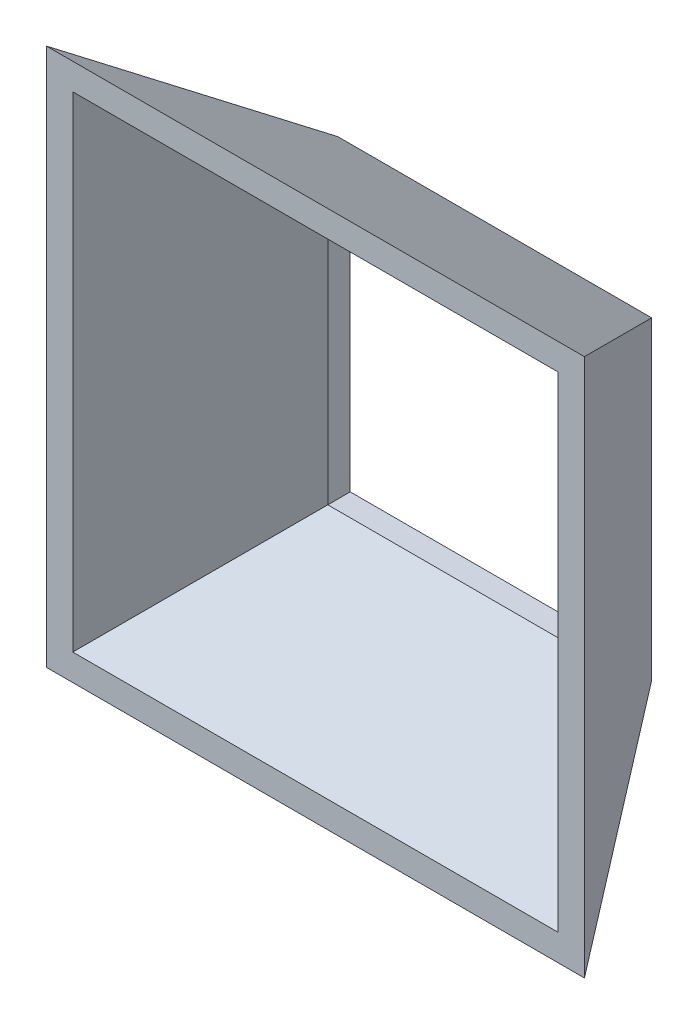
SolidWorks part; units mm, degrees
ref_plane "Front Plane" through (0, 0, 0) normal (0, 0, 1) x (1, 0, 0)
ref_plane "Top Plane" through (0, 0, 0) normal (0, 1, 0) x (1, 0, 0)
ref_plane "Right Plane" through (0, 0, 0) normal (1, 0, 0) x (0, 0, -1)
sketch "Sketch1" plane through (0, 0, 0) normal (0, 0, 1) x (1, 0, 0)
  line L0 (0, 0) -> (0, 0.6682) construction
  line L1 (-44.45, 44.45) -> (44.45, 44.45)
  line L2 (-44.45, 44.45) -> (-44.45, -44.45)
  line L3 (-44.45, -44.45) -> (44.45, -44.45)
  line L4 (44.45, 44.45) -> (44.45, -44.45)
  line L5 (0, 0) -> (0.3971, 0) construction
  dimension "D1" = 88.9
ref_plane "TopFunnelPlane" through (0, 0, 50.8) normal (0, 0, 1) x (1, 0, 0)
sketch "Sketch2" plane through (0, 0, 50.8) normal (0, 0, 1) x (1, 0, 0)
  line L0 (0, 0) -> (0, -1.7768) construction
  line L1 (-76.2, 76.2) -> (76.2, 76.2)
  line L2 (-76.2, 76.2) -> (-76.2, -76.2)
  line L3 (-76.2, -76.2) -> (76.2, -76.2)
  line L4 (76.2, 76.2) -> (76.2, -76.2)
  line L5 (0, 0) -> (1.7854, 0) construction
  dimension "D1" = 152.4
loft "Loft1" add profiles "Sketch1", "Sketch2"
shell "Shell1" thickness 6.35
sketch "Sketch4" plane through (0, 0, 6.35) normal (0, 0, 1) x (1, 0, 0)
  line L1 (-40.9305, -40.9305) -> (40.9305, -40.9305)
  line L2 (-40.9305, -40.9305) -> (-40.9305, 40.9305)
  line L3 (-40.9305, 40.9305) -> (40.9305, 40.9305)
  line L4 (40.9305, -40.9305) -> (40.9305, 40.9305)
extrude "Cut-Extrude1" cut sketch "Sketch4" against normal through all
